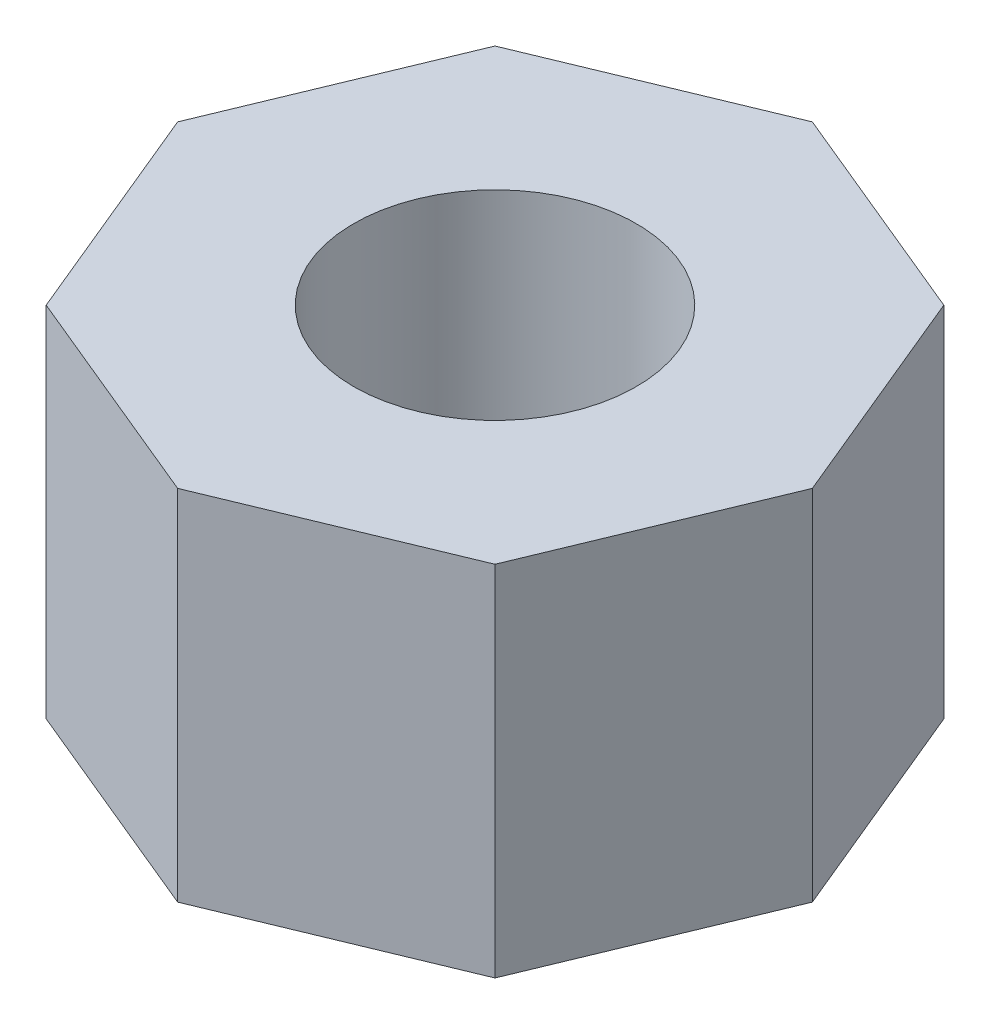
SolidWorks part; units mm, degrees
ref_plane "Front Plane" through (0, 0, 0) normal (0, 0, 1) x (1, 0, 0)
ref_plane "Top Plane" through (0, 0, 0) normal (0, 1, 0) x (1, 0, 0)
ref_plane "Right Plane" through (0, 0, 0) normal (1, 0, 0) x (0, 0, -1)
sketch "Sketch1" plane through (0, 0, 0) normal (0, 1, 0) x (1, 0, 0)
  line L1 (0, 3.937) -> (-2.7839, 2.7839)
  line L2 (-2.7839, 2.7839) -> (-3.937, 0)
  line L3 (-3.937, 0) -> (-2.7839, -2.7839)
  line L4 (-2.7839, -2.7839) -> (0, -3.937)
  line L5 (0, -3.937) -> (2.7839, -2.7839)
  line L6 (2.7839, -2.7839) -> (3.937, 0)
  line L7 (3.937, 0) -> (2.7839, 2.7839)
  line L8 (2.7839, 2.7839) -> (0, 3.937)
  circle A0 centre (0, 0) radius 3.6373 construction
  circle A1 centre (0, 0) radius 1.7526
  dimension "D2" = 3.5052
  dimension "D1" = 7.874
extrude "Boss-Extrude1" add sketch "Sketch1" along normal blind 4.445
